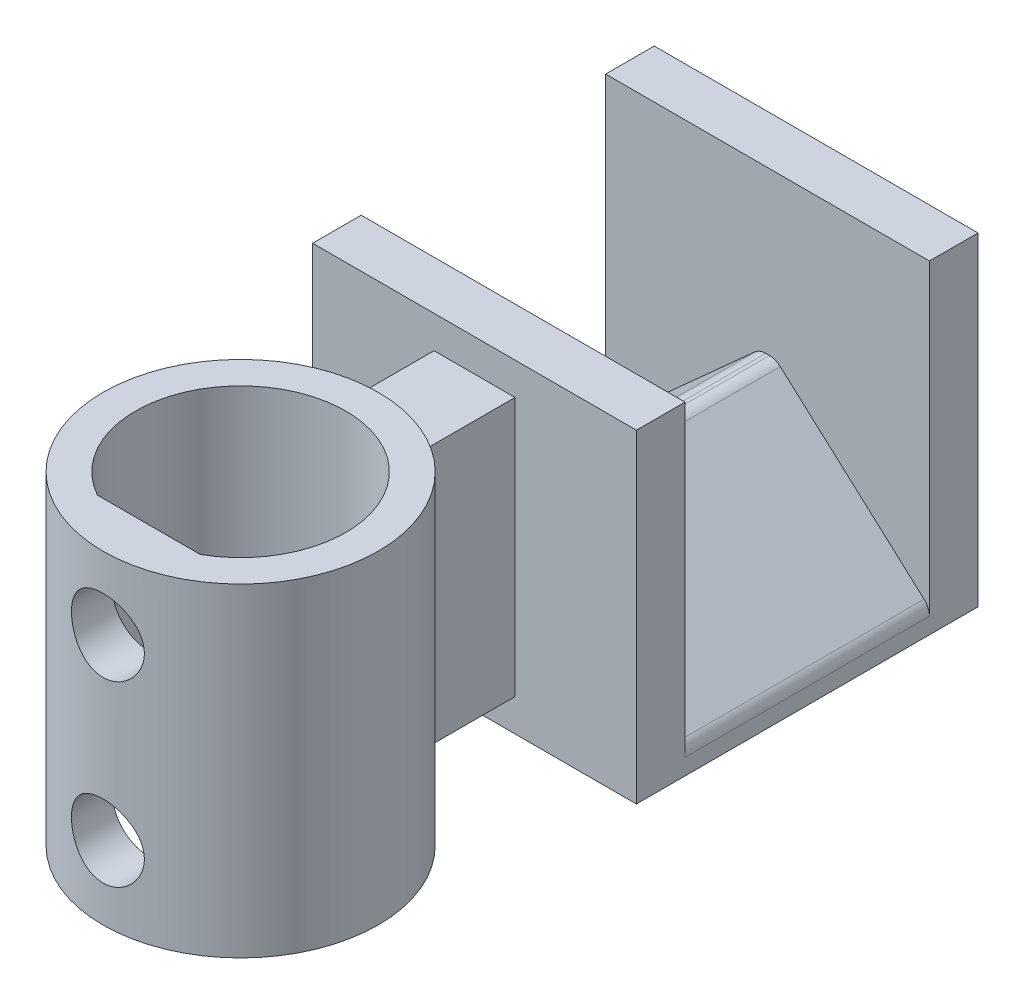
SolidWorks part; units mm, degrees
material "ABS"
ref_plane "Front Plane" through (0, 0, 0) normal (0, 0, 1) x (1, 0, 0)
ref_plane "Top Plane" through (0, 0, 0) normal (0, 1, 0) x (1, 0, 0)
ref_plane "Right Plane" through (0, 0, 0) normal (1, 0, 0) x (0, 0, -1)
sketch "Sketch2" plane through (0, 0, 0) normal (0, 0, 1) x (1, 0, 0)
  line L1 (-10, -5) -> (10, -5)
  line L2 (-10, -5) -> (-10, 5)
  line L3 (-10, 5) -> (10, 5)
  line L4 (10, -5) -> (10, 5)
  line L5 (-10, -5) -> (10, 5) construction
  line L6 (-10, 5) -> (10, -5) construction
  point P0 (0, 0)
  dimension "D1" = 10
  dimension "D2" = 20
extrude "Boss-Extrude1" add sketch "Sketch2" along normal mid plane 15.1
chamfer "Chamfer1" distance 9.5 angle 42 2 edges at (10, 5, 0) (-10, 5, 0)
fillet "Fillet3" radius 1 4 edges at (-10, -3.5538, 0) (10, -3.5538, 0) (0.5, 5, 0) (-0.5, 5, 0)
sketch "Sketch3" plane through (0, 0, 7.55) normal (0, 0, 1) x (1, 0, 0)
  line L0 (-10, -5) -> (10, -5) construction
  line L1 (-10, 15) -> (10, 15)
  line L2 (-10, 15) -> (-10, -5)
  line L3 (-10, -5) -> (10, -5)
  line L4 (10, 15) -> (10, -5)
  line L5 (-10, 15) -> (10, -5) construction
  line L6 (-10, -5) -> (10, 15) construction
  point P0 (0, 5)
  dimension "D1" = 20
  dimension "D2" = 20
extrude "Boss-Extrude2" add sketch "Sketch3" along normal blind 3
mirror "Mirror1" about plane through (0, 0, 0) normal (0, 0, 1) of "Boss-Extrude2"
sketch "Sketch6" plane through (0, 0, 0) normal (0, 1, 0) x (1, 0, 0)
  line L0 (3.175, -30.6718) -> (-3.175, -30.6718)
  arc A0 (3.175, -30.6718) -> (-3.175, -30.6718) centre (0, -25) ccw
  circle A1 centre (0, -25) radius 8.5
  dimension "D1" = 13
  dimension "D2" = 2
  dimension "D3" = 25
  dimension "D4" = 6.35
extrude "Boss-Extrude3" add sketch "Sketch6" along normal up to surface and the other way up to surface separate body up to face at (0, 15, 9.05) other way up to face at (0, -5, 0)
sketch "Sketch5" plane through (0, 0, 10.55) normal (0, 0, 1) x (1, 0, 0)
  line L0 (-10, -5) -> (10, -5) construction
  line L1 (-2.5, 13) -> (2.5, 13)
  line L2 (-2.5, 13) -> (-2.5, -3)
  line L3 (-2.5, -3) -> (2.5, -3)
  line L4 (2.5, 13) -> (2.5, -3)
  line L5 (-2.5, 13) -> (2.5, -3) construction
  line L6 (-2.5, -3) -> (2.5, 13) construction
  line L7 (10, 15) -> (-10, 15) construction
  point P0 (0, 5)
  dimension "D1" = 2
  dimension "D2" = 2
  dimension "D3" = 5
extrude "Boss-Extrude4" add sketch "Sketch5" along normal up to surface (6.326 mm away)
ref_plane "Plane1" through (0, 0, 20) normal (0, 0, 1) x (1, 0, 0)
sketch "Sketch7" plane through (0, 0, 20) normal (0, 0, 1) x (1, 0, 0)
  line L0 (-8.5, -5) -> (8.5, -5) construction
  line L1 (6.5, 15) -> (-6.5, 15) construction
  circle A0 centre (0, 10.5) radius 2.25
  circle A1 centre (0, -0.5) radius 2.25
  dimension "D1" = 4.5
  dimension "D2" = 4.5
  dimension "D3" = 4.5
  dimension "D4" = 4.5
extrude "Cut-Extrude1" cut sketch "Sketch7" along normal up to surface (13.1968 mm away)
